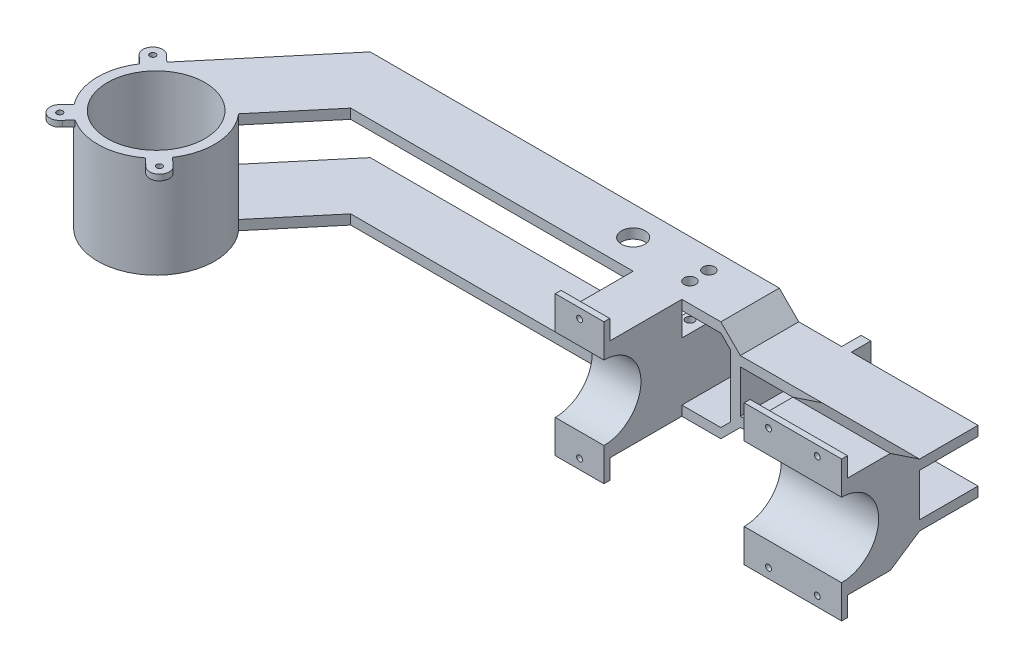
SolidWorks part; units mm, degrees
ref_plane "Front Plane" through (0, 0, 0) normal (0, 0, 1) x (1, 0, 0)
ref_plane "Top Plane" through (0, 0, 0) normal (0, 1, 0) x (1, 0, 0)
ref_plane "Right Plane" through (0, 0, 0) normal (1, 0, 0) x (0, 0, -1)
sketch "Sketch1" plane through (0, 0, 0) normal (0, 1, 0) x (1, 0, 0)
  line L3 (0, 15) -> (60, 15)
  line L4 (0, -15) -> (60, -15)
  line L5 (60, -15) -> (60, 15)
  circle A0 centre (0, 0) radius 6
  arc A2 (0, 15) -> (0, -15) centre (0, 0) ccw
extrude "Boss-Extrude4" add sketch "Sketch1" along normal blind 5
sketch "Sketch8" plane through (0, 0, 15) normal (0, 0, 1) x (1, 0, 0)
  line L0 (0, 0) -> (0, -21) construction
  line L1 (0, -21) -> (118.0272, -21) construction
  line L2 (60, 0) -> (60, -21) construction
  line L3 (60, -21) -> (70, -21) construction
  line L4 (70, -21) -> (70, -10) construction
  line L5 (60, 0) -> (70, -10)
  line L6 (70, -10) -> (110, -10)
  line L7 (110, -10) -> (110, -5)
  line L8 (110, -5) -> (70, -5)
  line L9 (70, -5) -> (60, 5)
  line L10 (60, 5) -> (60, 0)
extrude "Boss-Extrude5" add sketch "Sketch8" against normal blind 30
sketch "Sketch9" plane through (0, 0, 15) normal (0, 0, 1) x (1, 0, 0)
  line L0 (110, -10) -> (110, -21) construction
  line L1 (70, -10) -> (70, -21)
  line L2 (70, -21) -> (65, -21)
  line L3 (65, -21) -> (65, -5)
  line L4 (60, 0) -> (70, -10) construction
  line L5 (65, -5) -> (70, -10)
extrude "Boss-Extrude6" add sketch "Sketch9" against normal blind 30
mirror "Mirror3" about plane through (70, -21, -15) normal (0, -1, 0) of "Boss-Extrude6"
ref_plane "Plane2" through (0, -21, 0) normal (0, -1, 0) x (-1, 0, 0)
sketch "Sketch10" plane through (0, 0, 15) normal (0, 0, 1) x (1, 0, 0)
  line L0 (70, -21) -> (-15.976, -21) construction
  line L1 (70, -32) -> (70, -10) construction
  line L2 (-16.5, -21) -> (16.5, -21) construction
ref_plane "Plane3" through (0, -42, 0) normal (0, -1, 0) x (-1, 0, 0)
sketch "Sketch11" plane through (0, -42, 0) normal (0, -1, 0) x (-1, 0, 0)
  line L0 (0, 15) -> (-60, 15)
  line L1 (-60, 15) -> (-60, -15)
  line L2 (-60, -15) -> (0, -15)
  arc A0 (0, -15) -> (0, 15) centre (0, 0) ccw
  circle A1 centre (0, 0) radius 6
extrude "Boss-Extrude7" add sketch "Sketch11" along normal blind 5 separate body
sketch "Sketch12" plane through (0, 0, -15) normal (0, 0, -1) x (-1, 0, 0)
  line L2 (-70, -10) -> (-110, -10) construction
  line L4 (-110, -5) -> (-70, -5) construction
  line L6 (-70, -5) -> (-60, 5) construction
  line L8 (-60, 0) -> (-65, -5) construction
  line L12 (-16.5, -21) -> (16.5, -21) construction
  line L13 (-70, -32) -> (-65, -37)
  line L14 (-60, -47) -> (-60, -42)
  line L15 (-60, -42) -> (-65, -37)
  line L16 (-70, -37) -> (-60, -47)
  line L17 (-110, -37) -> (-70, -37)
  line L18 (-70, -32) -> (-110, -32)
  line L19 (-110, -32) -> (-110, -37)
extrude "Boss-Extrude8" add sketch "Sketch12" against normal blind 30
sketch "Sketch13" plane through (0, 0, -15) normal (0, 0, -1) x (-1, 0, 0)
  line L0 (-110, -10) -> (-97, -10) construction
  line L1 (-70, -10) -> (-110, -10) construction
  line L2 (-97, -10) -> (-97, -37)
  line L3 (-110, -37) -> (-70, -37) construction
  line L4 (-97, -37) -> (-92, -37)
  line L5 (-92, -37) -> (-92, -5)
  line L6 (-110, -5) -> (-70, -5) construction
  line L7 (-92, -5) -> (-97, -5)
  line L8 (-97, -5) -> (-97, -10)
extrude "Boss-Extrude9" add sketch "Sketch13" along normal blind 10
sketch "Sketch14" plane through (97, 0, 0) normal (1, 0, 0) x (0, 0, -1)
  line L0 (20.5314, -21) -> (19.3, -21) construction
  line L1 (15, -10) -> (15, -32) construction
  line L2 (15, -15) -> (19.3, -15) construction
  line L3 (25, -21) -> (20.5314, -21) construction
  line L4 (25, -5) -> (25, -37) construction
  line L5 (-16.5, -21) -> (16.5, -21) construction
  line L6 (19.3, -21) -> (19.3, -16.05) construction
  circle A2 centre (19.3, -16.05) radius 2.2
  circle A3 centre (19.3, -25.95) radius 2.2
extrude "Cut-Extrude2" cut sketch "Sketch14" against normal up to next
sketch "Sketch16" plane through (0, -47, 0) normal (0, -1, 0) x (1, 0, 0)
  line L0 (60, 15) -> (40, 15) construction
  line L1 (70, 15) -> (-15.976, 15) construction
  line L2 (40, 15) -> (40, 55)
  line L3 (40, 55) -> (15, 55)
  line L4 (15, 55) -> (15, 15)
  line L5 (15, 15) -> (40, 15)
  dimension "D1" = 40
  dimension "D2" = 25
  dimension "D3" = 20
extrude "Boss-Extrude10" add sketch "Sketch16" against normal blind 52
sketch "Sketch18" plane through (40, 0, 0) normal (1, 0, 0) x (0, 0, -1)
  line L0 (-55, 5) -> (-55, -47) construction
  circle A0 centre (-55, -21) radius 19
extrude "Cut-Extrude4" cut sketch "Sketch18" against normal up to next
sketch "Sketch19" plane through (110, 0, 0) normal (1, 0, 0) x (0, 0, -1)
  line L0 (15, -32) -> (15, -37) construction
  line L1 (-15, -5) -> (15, -5)
  line L2 (-15, -5) -> (-15, -10)
  line L3 (-15, -10) -> (15, -10)
  line L4 (15, -5) -> (15, -10)
  line L5 (-15, -32) -> (15, -32)
  line L6 (-15, -32) -> (-15, -37)
  line L7 (-15, -37) -> (15, -37)
  line L8 (15, -32) -> (15, -37)
extrude "Boss-Extrude11" add sketch "Sketch19" along normal blind 52
sketch "Sketch20" plane through (162, 0, 0) normal (1, 0, 0) x (0, 0, -1)
  line L0 (-55, 5) -> (-55, -2) construction
  line L1 (-55, 5) -> (-55, -2)
  line L2 (-55, -40) -> (-55, -47) construction
  line L3 (-55, -40) -> (-55, -47)
  line L4 (-55, 5) -> (-30, 5)
  line L5 (-15, 5) -> (-55, 5) construction
  line L6 (-30, 5) -> (-15, -5)
  line L7 (-15, -5) -> (-15, -37)
  line L8 (-15, -37) -> (-30, -47)
  line L9 (-15, -47) -> (-55, -47) construction
  line L10 (-30, -47) -> (-55, -47)
  arc A0 (-55, -40) -> (-55, -2) centre (-55, -21) ccw construction
  arc A1 (-55, -40) -> (-55, -2) centre (-55, -21) ccw
extrude "Boss-Extrude12" add sketch "Sketch20" against normal blind 50
sketch "Sketch21" plane through (0, 0, 55) normal (0, 0, 1) x (1, 0, 0)
  line L4 (15, 15) -> (15, 5)
  line L5 (15, 5) -> (40, 5)
  line L6 (40, 5) -> (40, 15)
  line L7 (40, 15) -> (15, 15)
  line L8 (15, 15) -> (15, 5)
  line L9 (15, 5) -> (40, 5)
  line L10 (40, 5) -> (40, 15)
  line L11 (40, 15) -> (15, 15)
  line L12 (15, -57) -> (40, -57)
  line L13 (40, -57) -> (40, -47)
  line L14 (40, -47) -> (15, -47)
  line L15 (15, -47) -> (15, -57)
  line L16 (15, -57) -> (40, -57)
  line L17 (40, -57) -> (40, -47)
  line L18 (40, -47) -> (15, -47)
  line L19 (15, -47) -> (15, -57)
  line L20 (162, 5) -> (162, 15)
  line L21 (162, 15) -> (112, 15)
  line L22 (112, 15) -> (112, 5)
  line L23 (112, 5) -> (162, 5)
  line L24 (162, 5) -> (162, 15)
  line L25 (162, 15) -> (112, 15)
  line L26 (112, 15) -> (112, 5)
  line L27 (112, 5) -> (162, 5)
  line L28 (162, -47) -> (112, -47)
  line L29 (112, -47) -> (112, -57)
  line L30 (112, -57) -> (162, -57)
  line L31 (162, -57) -> (162, -47)
  line L32 (162, -47) -> (112, -47)
  line L33 (112, -47) -> (112, -57)
  line L34 (112, -57) -> (162, -57)
  line L35 (162, -57) -> (162, -47)
  circle A0 centre (27.5, 10) radius 1.5 construction
  circle A1 centre (27.5, 10) radius 1.5
  circle A2 centre (124.5, 10) radius 1.5 construction
  circle A3 centre (124.5, 10) radius 1.5
  circle A4 centre (27.5, -52) radius 1.5 construction
  circle A5 centre (124.5, -52) radius 1.5 construction
  circle A6 centre (149.5, -52) radius 1.5 construction
  circle A7 centre (149.5, 10) radius 1.5 construction
  circle A8 centre (27.5, -52) radius 1.5
  circle A9 centre (124.5, -52) radius 1.5
  circle A10 centre (149.5, -52) radius 1.5
  circle A11 centre (149.5, 10) radius 1.5
  dimension "D1" = 0
  dimension "D2" = 0
  dimension "D3" = 0
  dimension "D4" = 0
sketch "Sketch22" plane through (0, 0, -15) normal (0, 0, -1) x (-1, 0, 0)
  line L0 (-30, -42) -> (-30, -12.1709)
  line L1 (0, -42) -> (-60, -42) construction
  line L2 (-30, -12.1709) -> (-40, -12.1709)
  line L3 (-40, 0) -> (-40, -42) construction
  line L4 (-40, -12.1709) -> (-40, -42)
  line L5 (-40, -42) -> (-30, -42)
extrude "Boss-Extrude14" add sketch "Sketch22" against normal up to next
sketch "Sketch24" plane through (0, 5, 0) normal (0, 1, 0) x (1, 0, 0)
  line L0 (60, 15) -> (0, 15) construction
  line L1 (23.2783, 15) -> (42.1396, 15)
  line L2 (23.2783, 15) -> (23.2783, -11.1566)
  line L3 (23.2783, -11.1566) -> (42.1396, -11.1566)
  line L4 (42.1396, 15) -> (42.1396, -11.1566)
sketch "Sketch25" plane through (0, -12.1709, 0) normal (0, 1, 0) x (1, 0, 0)
  circle A0 centre (34, 4.85) radius 2.0898
  circle A1 centre (34, -4.85) radius 2.15
sketch "Sketch26" plane through (0, 5, 0) normal (0, 1, 0) x (1, 0, 0)
  circle A0 centre (34, -4.85) radius 2.15 construction
  circle A1 centre (34, 4.85) radius 2.0898 construction
  circle A2 centre (34, -4.85) radius 2.15
  circle A3 centre (34, 4.85) radius 2.0898
extrude "Cut-Extrude6" cut sketch "Sketch26" against normal blind 33
sketch "Sketch27" plane through (0, 5, 0) normal (0, 1, 0) x (1, 0, 0)
  circle A0 centre (34, 4.85) radius 3
  circle A1 centre (34, -4.85) radius 3
extrude "Cut-Extrude7" cut sketch "Sketch27" against normal up to next
extrude "Boss-Extrude15" add sketch "Sketch21" against normal blind 3
sketch "Sketch28" plane through (0, -47, 0) normal (0, -1, 0) x (1, 0, 0)
  line L0 (0, 15) -> (0, 6)
  line L1 (0, 6) -> (-6, 6)
  line L2 (-6, 6) -> (-6, -6)
  line L3 (-6, -6) -> (0, -6)
  line L4 (0, -6) -> (0, -15)
  line L5 (0, -15) -> (-150, -15)
  line L6 (0, 0) -> (-70, 0) construction
  line L7 (-150, -15) -> (-201.423, 46.2836)
  line L8 (0, 15) -> (-130, 15)
  line L9 (-130, 15) -> (-156.25, 46.2836)
  line L10 (-201.423, 46.2836) -> (-156.25, 46.2836) construction
  circle A0 centre (0, 0) radius 6 construction
  arc A2 (-201.423, 46.2836) -> (-156.25, 46.2836) centre (-178.8365, 66.0282) ccw
  circle A3 centre (-178.8365, 66.0282) radius 30 construction
  dimension "D1" = 130
  dimension "D2" = 130
extrude "Boss-Extrude16" add sketch "Sketch28" against normal blind 5
sketch "Sketch29" plane through (0, 0, 15) normal (0, 0, 1) x (1, 0, 0)
  line L0 (60, 5) -> (60, -47) construction
  line L1 (60, -21) -> (49.0688, -21) construction
ref_plane "Plane4" through (0, -21, 0) normal (0, -1, 0) x (-1, 0, 0)
mirror "Mirror4" about plane through (0, -21, 0) normal (0, -1, 0) of "Boss-Extrude16"
sketch "Sketch30" plane through (0, -47, 0) normal (0, -1, 0) x (1, 0, 0)
  circle A0 centre (-178.8365, 66.0282) radius 30
  circle A1 centre (-178.8365, 66.0282) radius 25
extrude "Boss-Extrude17" add sketch "Sketch30" against normal up to vertex
sketch "Sketch31" plane through (0, 5, 0) normal (0, 1, 0) x (1, 0, 0)
  line L0 (-178.8365, -66.0282) -> (-148.8365, -66.0282) construction
  line L1 (-178.8365, -66.0282) -> (-153.2468, -89.9063) construction
  line L2 (-160.5664, -89.8232) -> (-157.209, -92.956)
  line L3 (-153.8356, -82.6099) -> (-150.4782, -85.7427)
  circle A0 centre (-178.8365, -66.0282) radius 25 construction
  circle A1 centre (-178.8365, -66.0282) radius 25 construction
  arc A2 (-201.423, -46.2836) -> (-156.25, -46.2836) centre (-178.8365, -66.0282) ccw construction
  circle A3 centre (-153.2468, -89.9063) radius 1.5
  arc A4 (-157.209, -92.956) -> (-150.4782, -85.7427) centre (-153.2468, -89.9063) ccw
  arc A5 (-160.5664, -89.8232) -> (-153.8356, -82.6099) centre (-178.8365, -66.0282) ccw
extrude "Boss-Extrude18" add sketch "Sketch31" against normal blind 3
pattern_circular "CirPattern1" count 3 every 90 about axis through (-178.8365, 0, 66.0282) along (0, 1, 0) of "Boss-Extrude18"
